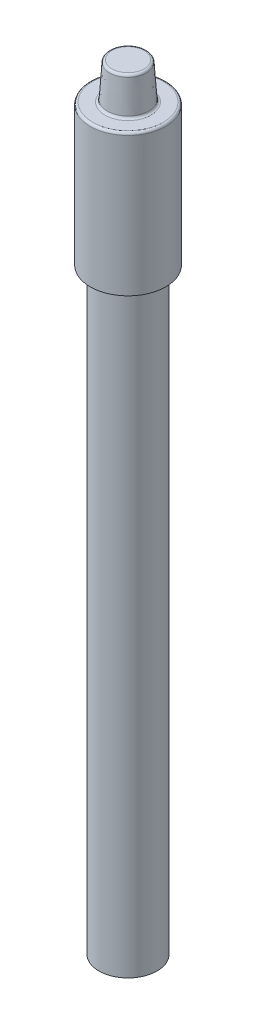
SolidWorks part; units mm, degrees
ref_plane "Front Plane" through (0, 0, 0) normal (0, 0, 1) x (1, 0, 0)
ref_plane "Top Plane" through (0, 0, 0) normal (0, 1, 0) x (1, 0, 0)
ref_plane "Right Plane" through (0, 0, 0) normal (1, 0, 0) x (0, 0, -1)
sketch "Sketch1" plane through (0, 0, 0) normal (0, 0, 1) x (1, 0, 0)
  line L0 (0, 0) -> (0, 161.544) construction
  line L1 (0, 161.544) -> (3.81, 161.544)
  line L2 (3.81, 161.544) -> (4.318, 153.924)
  line L3 (4.318, 153.924) -> (7.874, 153.924)
  line L4 (7.874, 153.924) -> (7.874, 124.46)
  line L5 (7.874, 124.46) -> (6.0579, 124.46)
  line L6 (6.0579, 124.46) -> (6.0579, 0)
  line L7 (6.0579, 0) -> (0, 0)
  line L8 (0, 161.544) -> (0, 0)
  dimension "D1" = 7.62
  dimension "D2" = 8.636
  dimension "D3" = 7.62
  dimension "D4" = 15.748
  dimension "D5" = 29.464
  dimension "D6" = 124.46
  dimension "D7" = 6.0579
revolve "Revolve1" add sketch "Sketch1" angle 360 about L0
sketch "Sketch2" plane through (0, 0, 0) normal (0, 0, 1) x (1, 0, 0)
  line L0 (0, 161.544) -> (0, 0) construction
  line L1 (3.81, 161.544) -> (-3.81, 161.544) construction
  line L2 (0, 7.9375) -> (0, 10.8585) construction
  line L3 (-1.5875, 7.9375) -> (-1.5875, 10.8585)
  line L4 (1.5875, 7.9375) -> (1.5875, 10.8585)
  line L5 (-6.0579, 0) -> (6.0579, 0) construction
  arc A0 (-1.5875, 7.9375) -> (1.5875, 7.9375) centre (0, 7.9375) ccw
  arc A1 (1.5875, 10.8585) -> (-1.5875, 10.8585) centre (0, 10.8585) ccw
  point P7 (0, 9.398)
  dimension "D2" = 1.5875
  dimension "D1" = 2.921
  dimension "D3" = 7.9375
extrude "Cut-Extrude1" cut sketch "Sketch2" against normal through all
fillet "Fillet1" radius 0.508 3 edges at (0, 161.544, -3.81) (0, 153.924, -7.874) (0, 153.924, -4.318)
